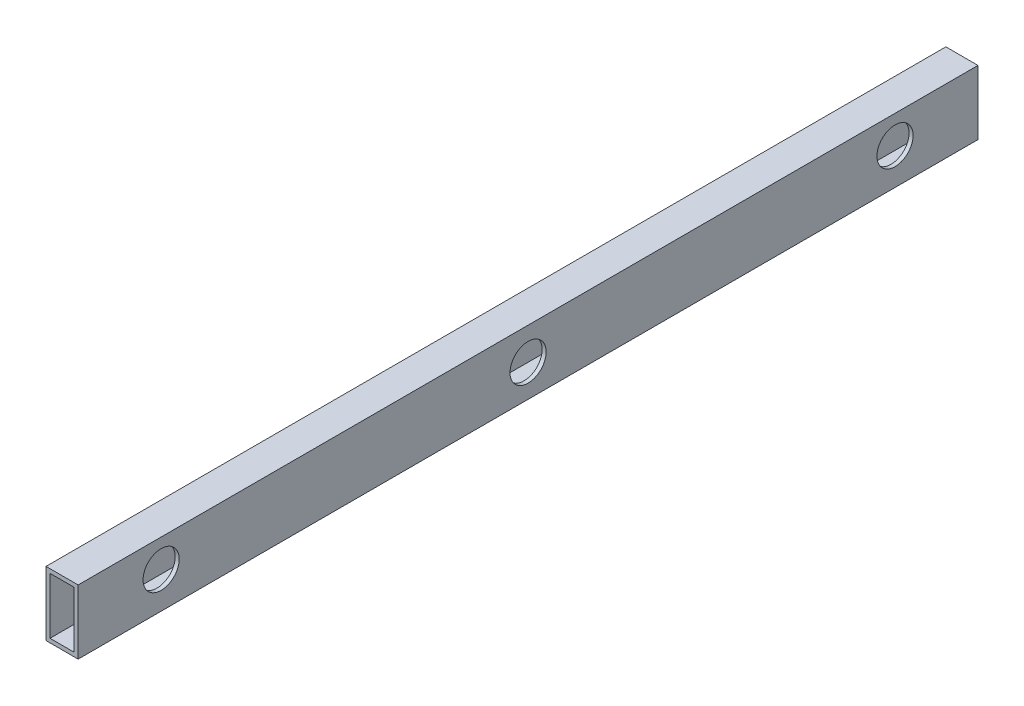
SolidWorks part; units mm, degrees
material "6061-T6 (SS)"
ref_plane "Front Plane" through (0, 0, 0) normal (0, 0, 1) x (1, 0, 0)
ref_plane "Top Plane" through (0, 0, 0) normal (0, 1, 0) x (1, 0, 0)
ref_plane "Right Plane" through (0, 0, 0) normal (1, 0, 0) x (0, 0, -1)
sketch "Sketch1" plane through (0, 0, 0) normal (0, 0, 1) x (1, 0, 0)
  line L0 (292.1, 25.4) -> (266.7, 25.4) construction
  line L1 (266.7, -25.4) -> (266.7, 25.4) construction
  line L2 (292.1, -25.4) -> (266.7, -25.4) construction
  line L3 (292.1, -25.4) -> (292.1, 25.4) construction
  line L4 (292.1, 25.4) -> (266.7, 25.4)
  line L5 (266.7, -25.4) -> (266.7, 25.4)
  line L6 (292.1, -25.4) -> (266.7, -25.4)
  line L7 (292.1, -25.4) -> (292.1, 25.4)
  line L8 (288.925, 22.225) -> (269.875, 22.225)
  line L9 (269.875, -22.225) -> (269.875, 22.225)
  line L10 (288.925, -22.225) -> (269.875, -22.225)
  line L11 (288.925, -22.225) -> (288.925, 22.225)
  dimension "D1" = 3.175
extrude "Boss-Extrude1" add sketch "Sketch1" along normal up to vertex (355.6 mm away) and the other way up to vertex (355.6 mm away)
sketch "Sketch2" plane through (0, 0, 0) normal (1, 0, 0) x (0, 0, -1)
  circle A0 centre (290.0074, 3.175) radius 14.2875 construction
  circle A1 centre (0, 0) radius 14.2875 construction
  circle A2 centre (-290.0074, 3.175) radius 14.2875 construction
  circle A3 centre (290.0074, 3.175) radius 14.2875
  circle A4 centre (0, 0) radius 14.2875
  circle A5 centre (-290.0074, 3.175) radius 14.2875
extrude "Cut-Extrude1" cut sketch "Sketch2" along normal through all
